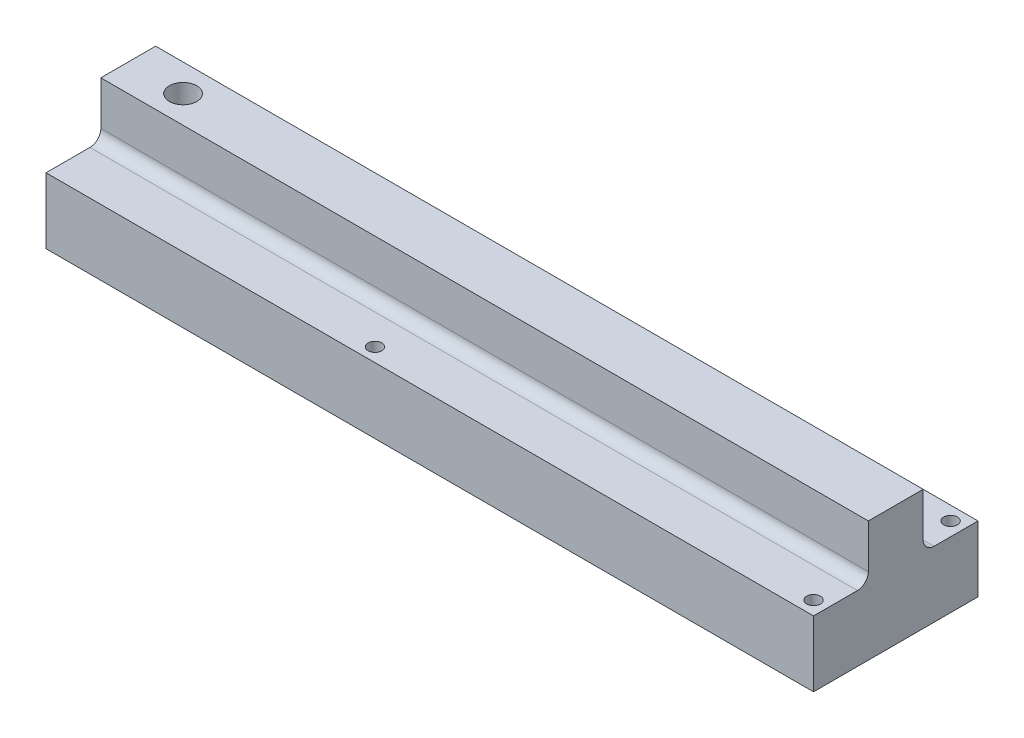
SolidWorks part; units mm, degrees
ref_plane "Front Plane" through (0, 0, 0) normal (0, 0, 1) x (1, 0, 0)
ref_plane "Top Plane" through (0, 0, 0) normal (0, 1, 0) x (1, 0, 0)
ref_plane "Right Plane" through (0, 0, 0) normal (1, 0, 0) x (0, 0, -1)
sketch "Sketch1" plane through (0, 0, 0) normal (1, 0, 0) x (0, 0, -1)
  line L0 (0, 0) -> (-60, 0)
  line L1 (-60, 0) -> (-60, 24)
  line L2 (-60, 24) -> (-40, 24)
  line L3 (-40, 24) -> (-40, 44)
  line L4 (-40, 44) -> (-20, 44)
  line L5 (-20, 44) -> (-20, 24)
  line L6 (-20, 24) -> (0, 24)
  line L7 (0, 24) -> (0, 0)
  point P5 (-30, 0)
  point P10 (-30, 44)
  point P11 (0, 0)
  dimension "D1" = 60
  dimension "D2" = 24
  dimension "D3" = 20
  dimension "D4" = 20
extrude "Boss-Extrude1" add sketch "Sketch1" along normal blind 280
sketch "Sketch3" plane through (0, 24, 0) normal (0, 1, 0) x (1, 0, 0)
  line L0 (0, -40) -> (0, -60) construction
  line L1 (280, -60) -> (0, -60) construction
  line L2 (0, -30) -> (280, -30) construction
  line L3 (0, -20) -> (0, -40) construction
  line L4 (280, -20) -> (280, -40) construction
  circle A0 centre (115, -55) radius 2.5
  circle A1 centre (275, -55) radius 2.5
  circle A2 centre (275, -5) radius 2.5
  circle A3 centre (115, -5) radius 2.5
  dimension "D1" = 5
  dimension "D2" = 5
  dimension "D3" = 115
  dimension "D4" = 160
  dimension "D5" = 5
  dimension "D6" = 5
extrude "Cut-Extrude2" cut sketch "Sketch3" against normal blind 8
fillet "Fillet1" radius 4 2 edges at (140, 24, 20) (140, 24, 40)
sketch "Sketch4" plane through (0, 44, 0) normal (0, 1, 0) x (1, 0, 0)
  line L0 (0, -20) -> (0, -40) construction
  circle A0 centre (20, -30) radius 5
  point P4 (0, -30)
  point P5 (0, 0)
  dimension "D1" = 10
  dimension "D2" = 20
extrude "Cut-Extrude3" cut sketch "Sketch4" against normal blind 10
